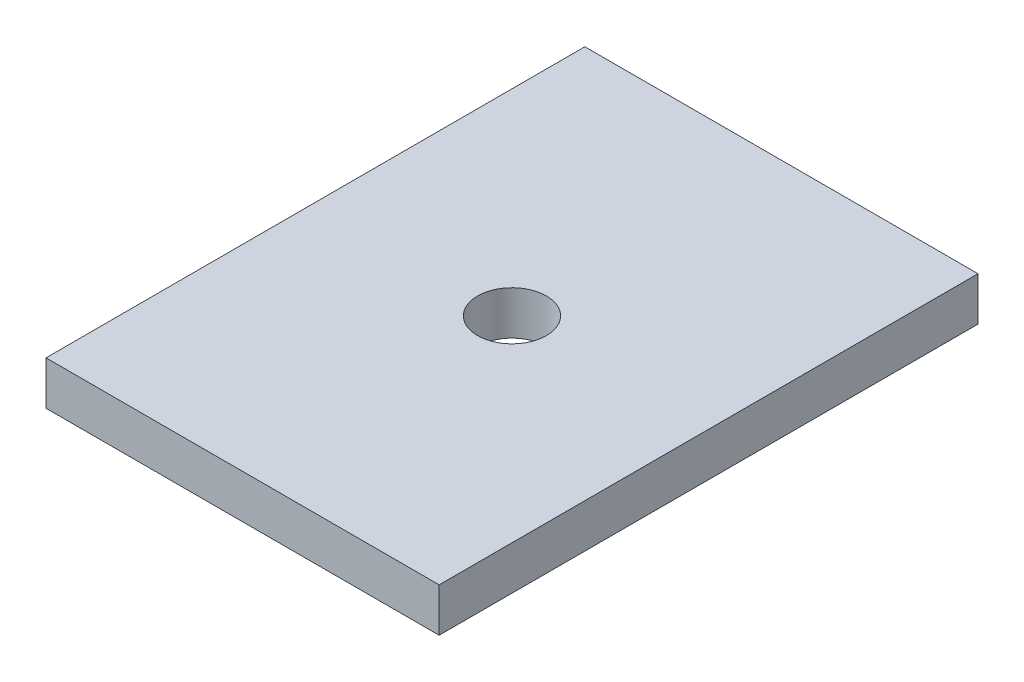
SolidWorks part; units mm, degrees
ref_plane "Front Plane" through (0, 0, 0) normal (0, 0, 1) x (1, 0, 0)
ref_plane "Top Plane" through (0, 0, 0) normal (0, 1, 0) x (1, 0, 0)
ref_plane "Right Plane" through (0, 0, 0) normal (1, 0, 0) x (0, 0, -1)
sketch "Sketch2" plane through (0, 0, 0) normal (0, 1, 0) x (1, 0, 0)
  line L1 (-85.725, -117.5) -> (85.725, -117.5)
  line L2 (-85.725, -117.5) -> (-85.725, 117.5)
  line L3 (-85.725, 117.5) -> (85.725, 117.5)
  line L4 (85.725, -117.5) -> (85.725, 117.5)
  line L5 (-85.725, -117.5) -> (85.725, 117.5) construction
  line L6 (-85.725, 117.5) -> (85.725, -117.5) construction
  circle A0 centre (0, 0) radius 15
  point P0 (0, 0)
  dimension "D2" = 30
  dimension "D1" = 235
extrude "Boss-Extrude3" add sketch "Sketch2" along normal blind 19.05
